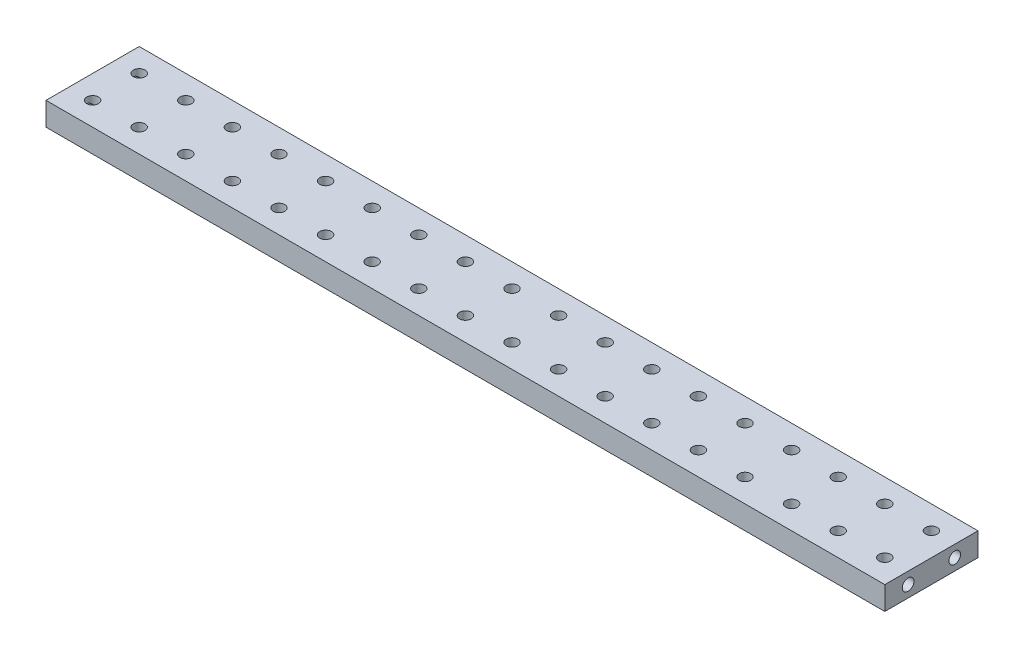
SolidWorks part; units mm, degrees
ref_plane "Front Plane" through (0, 0, 0) normal (0, 0, 1) x (1, 0, 0)
ref_plane "Top Plane" through (0, 0, 0) normal (0, 1, 0) x (1, 0, 0)
ref_plane "Right Plane" through (0, 0, 0) normal (1, 0, 0) x (0, 0, -1)
sketch "Sketch1" plane through (0, 0, 0) normal (0, 1, 0) x (1, 0, 0)
  line L1 (-228.6, -25.4) -> (228.6, -25.4)
  line L2 (-228.6, -25.4) -> (-228.6, 25.4)
  line L3 (-228.6, 25.4) -> (228.6, 25.4)
  line L4 (228.6, -25.4) -> (228.6, 25.4)
  line L5 (0, 25.4) -> (0, -25.4) construction
  line L6 (-228.6, 0) -> (228.6, 0) construction
  point P0 (0, 0)
  dimension "D1" = 50.8
  dimension "D2" = 457.2
extrude "Boss-Extrude1" add sketch "Sketch1" along normal blind 12.7
sketch "Sketch2" plane through (-228.6, 0, 0) normal (-1, 0, 0) x (0, 0, 1)
  line L0 (-25.4, 12.7) -> (-25.4, 0) construction
  circle A0 centre (-12.7, 6.35) radius 3.175
  circle A1 centre (12.7, 6.35) radius 3.175
  point P4 (-25.4, 6.35)
  dimension "D1" = 6.35
  dimension "D2" = 12.7
  dimension "D3" = 2
extrude "Cut-Extrude1" cut sketch "Sketch2" against normal blind 12.7
sketch "Sketch3" plane through (228.6, 0, 0) normal (1, 0, 0) x (0, 0, -1)
  line L1 (-25.4, 12.7) -> (-25.4, 0) construction
  circle A0 centre (-12.7, 6.35) radius 3.175
  circle A1 centre (12.7, 6.35) radius 3.175
  point P5 (-25.4, 6.35)
  dimension "D1" = 6.35
  dimension "D2" = 12.7
  dimension "D3" = 2
extrude "Cut-Extrude2" cut sketch "Sketch3" against normal blind 12.7
sketch "Sketch4" plane through (0, 12.7, 0) normal (0, 1, 0) x (1, 0, 0)
  line L0 (228.6, 25.4) -> (-228.6, 25.4) construction
  line L1 (-228.6, 25.4) -> (-228.6, -25.4) construction
  circle A0 centre (-215.9, 12.7) radius 3.175
  circle A1 centre (-190.5, 12.7) radius 3.175
  circle A2 centre (-165.1, 12.7) radius 3.175
  circle A3 centre (-139.7, 12.7) radius 3.175
  circle A4 centre (-114.3, 12.7) radius 3.175
  circle A5 centre (-88.9, 12.7) radius 3.175
  circle A6 centre (-63.5, 12.7) radius 3.175
  circle A7 centre (-38.1, 12.7) radius 3.175
  circle A8 centre (-12.7, 12.7) radius 3.175
  circle A9 centre (12.7, 12.7) radius 3.175
  circle A10 centre (38.1, 12.7) radius 3.175
  circle A11 centre (63.5, 12.7) radius 3.175
  circle A12 centre (88.9, 12.7) radius 3.175
  circle A13 centre (114.3, 12.7) radius 3.175
  circle A14 centre (139.7, 12.7) radius 3.175
  circle A15 centre (165.1, 12.7) radius 3.175
  circle A16 centre (190.5, 12.7) radius 3.175
  circle A17 centre (215.9, 12.7) radius 3.175
  circle A18 centre (241.3, 12.7) radius 3.175
  circle A19 centre (266.7, 12.7) radius 3.175
  circle A20 centre (292.1, 12.7) radius 3.175
  circle A21 centre (317.5, 12.7) radius 3.175
  circle A22 centre (342.9, 12.7) radius 3.175
  circle A23 centre (368.3, 12.7) radius 3.175
  circle A24 centre (-190.5, -12.7) radius 3.175
  circle A25 centre (-165.1, -12.7) radius 3.175
  circle A26 centre (-139.7, -12.7) radius 3.175
  circle A27 centre (-114.3, -12.7) radius 3.175
  circle A28 centre (-88.9, -12.7) radius 3.175
  circle A29 centre (-63.5, -12.7) radius 3.175
  circle A30 centre (-38.1, -12.7) radius 3.175
  circle A31 centre (-12.7, -12.7) radius 3.175
  circle A32 centre (12.7, -12.7) radius 3.175
  circle A33 centre (38.1, -12.7) radius 3.175
  circle A34 centre (63.5, -12.7) radius 3.175
  circle A35 centre (88.9, -12.7) radius 3.175
  circle A36 centre (114.3, -12.7) radius 3.175
  circle A37 centre (139.7, -12.7) radius 3.175
  circle A38 centre (165.1, -12.7) radius 3.175
  circle A39 centre (190.5, -12.7) radius 3.175
  circle A40 centre (215.9, -12.7) radius 3.175
  circle A41 centre (241.3, -12.7) radius 3.175
  circle A42 centre (266.7, -12.7) radius 3.175
  circle A43 centre (292.1, -12.7) radius 3.175
  circle A44 centre (317.5, -12.7) radius 3.175
  circle A45 centre (342.9, -12.7) radius 3.175
  circle A46 centre (368.3, -12.7) radius 3.175
  circle A47 centre (-215.9, -12.7) radius 3.175
  dimension "D1" = 6.35
  dimension "D2" = 12.7
  dimension "D3" = 12.7
  dimension "D4" = 24
  dimension "D5" = 2
extrude "Cut-Extrude3" cut sketch "Sketch4" against normal through all
